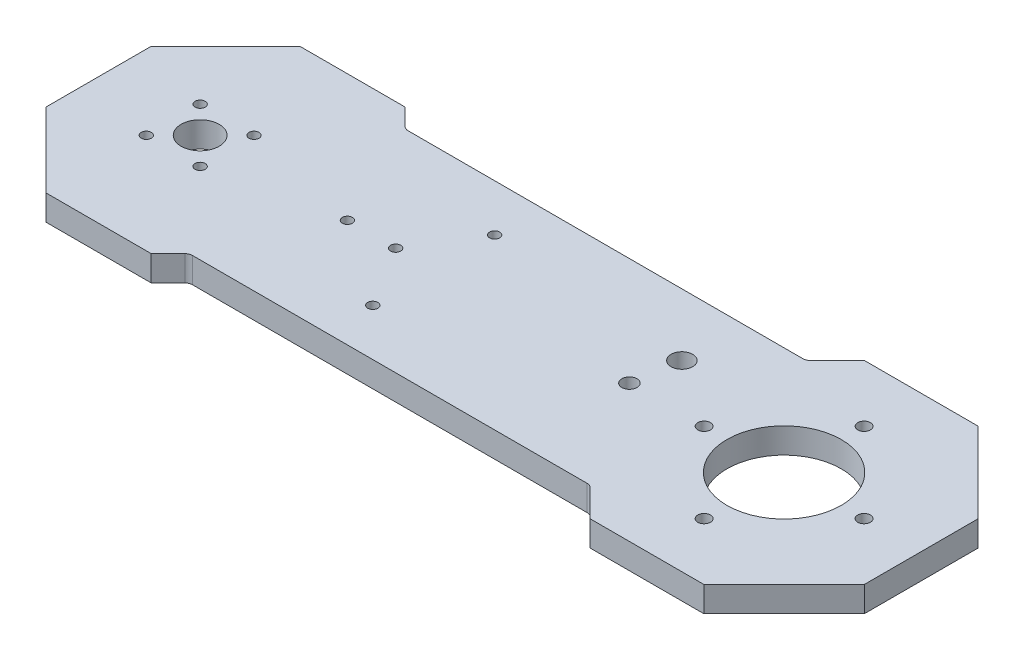
SolidWorks part; units mm, degrees
ref_plane "Спереди" through (0, 0, 0) normal (0, 0, 1) x (1, 0, 0)
ref_plane "Сверху" through (0, 0, 0) normal (0, 1, 0) x (1, 0, 0)
ref_plane "Справа" through (0, 0, 0) normal (1, 0, 0) x (0, 0, -1)
sketch "Эскиз1" plane through (0, 0, 0) normal (0, 1, 0) x (1, 0, 0)
  line L0 (-104.8938, 0) -> (200.5194, 0) construction
  line L1 (-172.6821, 42.5) -> (-12.3342, 42.5)
  line L2 (-172.6821, -42.5) -> (-12.3342, -42.5)
  line L4 (-172.6821, -42.5) -> (-172.6821, 42.5) construction
  arc A0 (-172.6821, 42.5) -> (-172.6821, -42.5) centre (-199.0213, 0) ccw
  arc A2 (-12.3342, -42.5) -> (-12.3342, 42.5) centre (20.9787, 0) ccw
  dimension "D1" = 220
  dimension "D2" = 108
  dimension "D3" = 100
  dimension "D4" = 85
extrude "Бобышка-Вытянуть1" add sketch "Эскиз1" along normal blind 10
sketch "Эскиз2" plane through (0, 10, 0) normal (0, 1, 0) x (1, 0, 0)
  line L0 (20.9787, 31.5) -> (20.9787, -31.5) construction
  line L1 (20.9787, -31.5) -> (52.4787, 0) construction
  line L2 (52.4787, 0) -> (-10.5213, 0) construction
  circle A0 centre (20.9787, 0) radius 31.5 construction
  circle A1 centre (20.9787, 31.5) radius 2.5
  circle A2 centre (-10.5213, 0) radius 2.5
  circle A3 centre (20.9787, -31.5) radius 2.5
  circle A4 centre (52.4787, 0) radius 2.5
  dimension "D1" = 63
  dimension "D2" = 5
  dimension "D3" = 5
  dimension "D4" = 5
  dimension "D5" = 5
extrude "Вырез-Вытянуть1" cut sketch "Эскиз2" against normal blind 10
chamfer "Фаска1" distance 2 angle 45 4 edges at (52.4787, 0, 2.5) (20.9787, 0, -29) (-10.5213, 0, 2.5) (20.9787, 0, 34)
sketch "Эскиз4" plane through (0, 0, 0) normal (0, -1, 0) x (1, 0, 0)
  circle A0 centre (20.9787, 0) radius 22.5
  dimension "D1" = 45
extrude "Вырез-Вытянуть3" cut sketch "Эскиз4" against normal blind 36
sketch "Эскиз6" plane through (0, 0, 0) normal (0, -1, 0) x (1, 0, 0)
  line L5 (-249.0213, 0) -> (74.9787, 0) construction
  arc A0 (-172.6821, 42.5) -> (-172.6821, -42.5) centre (-199.0213, 0) ccw construction
  arc A1 (-12.3342, -42.5) -> (-12.3342, 42.5) centre (20.9787, 0) ccw construction
  circle A2 centre (20.9787, 0) radius 22.5 construction
  circle A5 centre (-209.0213, 0) radius 7.5
  dimension "D1" = 230
  dimension "D7" = 15
sketch "Эскиз9" plane through (0, 10, 0) normal (0, 1, 0) x (1, 0, 0)
  line L0 (-39.952, -42.5) -> (-39.952, 42.5) construction
  line L1 (-172.6821, -42.5) -> (-12.3342, -42.5) construction
  line L2 (-12.3342, 42.5) -> (-172.6821, 42.5) construction
  line L3 (-39.952, 0) -> (-61.9777, 0) construction
  circle A0 centre (-39.952, 0) radius 3
  dimension "D1" = 6
extrude "Вырез-Вытянуть8" cut sketch "Эскиз9" against normal blind 13
sketch "Эскиз10" plane through (0, 10, 0) normal (0, 1, 0) x (1, 0, 0)
  circle A0 centre (-37.3333, 18.0546) radius 4.25
extrude "Вырез-Вытянуть9" cut sketch "Эскиз10" against normal blind 13
chamfer "Фаска6" distance 1 angle 45 1 edges at (-37.3333, 0, -13.8046)
extrude "Вырез-Вытянуть10" cut sketch "Эскиз6" against normal blind 10
sketch "Эскиз11" plane through (0, 0, 0) normal (0, -1, 0) x (1, 0, 0)
  line L0 (-117.0213, 24) -> (-117.0213, -24) construction
  line L1 (-209.0213, 0) -> (20.9787, 0) construction
  circle A0 centre (-117.0213, 24) radius 2
  circle A1 centre (-117.0213, -24) radius 2
  circle A2 centre (-209.0213, 0) radius 7.5 construction
  dimension "D1" = 4
  dimension "D2" = 4
  dimension "D3" = 48
  dimension "D4" = 24
  dimension "D5" = 92
extrude "Вырез-Вытянуть11" cut sketch "Эскиз11" against normal blind 15
sketch "Эскиз12" plane through (0, 0, 0) normal (0, -1, 0) x (1, 0, 0)
  line L1 (-209.0213, 0) -> (-132.0213, 0) construction
  circle A0 centre (-151.0213, 0) radius 2
  circle A1 centre (-132.0213, 0) radius 2
  circle A2 centre (-209.0213, 0) radius 7.5 construction
  dimension "D1" = 4
  dimension "D2" = 4
  dimension "D3" = 19
  dimension "D4" = 58
extrude "Вырез-Вытянуть12" cut sketch "Эскиз12" against normal blind 15
sketch "Эскиз13" plane through (0, 0, 0) normal (0, -1, 0) x (-1, 0, 0)
  line L0 (249.0213, 0) -> (-74.9787, 0) construction
  line L1 (209.0213, 15) -> (209.0213, -15) construction
  line L2 (209.0213, 0) -> (219.6279, 10.6066) construction
  line L3 (219.6279, 10.6066) -> (198.4147, 10.6066) construction
  line L4 (198.4147, 10.6066) -> (209.0213, 0) construction
  line L5 (209.0213, 0) -> (198.4147, -10.6066) construction
  line L6 (198.4147, -10.6066) -> (219.6279, -10.6066) construction
  line L7 (219.6279, -10.6066) -> (209.0213, 0) construction
  arc A0 (172.6821, -42.5) -> (172.6821, 42.5) centre (199.0213, 0) ccw construction
  arc A1 (12.3342, 42.5) -> (12.3342, -42.5) centre (-20.9787, 0) ccw construction
  circle A4 centre (219.6279, -10.6066) radius 2
  circle A5 centre (198.4147, -10.6066) radius 2
  circle A6 centre (219.6279, 10.6066) radius 2
  circle A7 centre (198.4147, 10.6066) radius 2
  circle A8 centre (209.0213, 0) radius 15 construction
  dimension "D1" = 45
  dimension "D5" = 4
  dimension "D6" = 4
  dimension "D7" = 4
  dimension "D8" = 4
  dimension "D9" = 30
extrude "Вырез-Вытянуть13" cut sketch "Эскиз13" against normal blind 10
sketch "Эскиз14" plane through (0, 0, 0) normal (0, -1, 0) x (-1, 0, 0)
  line L0 (249.0213, 0) -> (-74.9787, 0) construction
  line L1 (170.8106, -42.5) -> (12.8888, -42.5)
  line L2 (-43.3462, -54) -> (1.3888, -54)
  line L3 (1.3888, -54) -> (12.8888, -42.5)
  line L5 (12.8888, 42.5) -> (1.3888, 54)
  line L6 (1.3888, 54) -> (-43.3462, 54)
  line L7 (-43.3462, 54) -> (-74.9787, 22.3675)
  line L8 (-74.9787, 22.3675) -> (-74.9787, -22.3675)
  line L9 (-74.9787, -22.3675) -> (-43.3462, -54)
  line L10 (178.3106, -50) -> (219.732, -50)
  line L11 (219.732, -50) -> (249.0213, -20.7107)
  line L12 (249.0213, -20.7107) -> (249.0213, 20.7107)
  line L13 (249.0213, 20.7107) -> (219.732, 50)
  line L14 (219.732, 50) -> (178.3106, 50)
  line L15 (178.3106, 50) -> (170.8106, 42.5)
  line L17 (170.8106, -42.5) -> (178.3106, -50)
  line L18 (172.6821, -42.5) -> (12.3342, -42.5) construction
  line L19 (170.8106, 42.5) -> (12.8888, 42.5)
  line L20 (12.3342, 42.5) -> (172.6821, 42.5) construction
  line L24 (149.0213, 0) -> (149.0213, -20.7107) [skipped]
  line L25 (33.0213, -22.3675) -> (33.0213, 0) [skipped]
  arc A0 (172.6821, -42.5) -> (172.6821, 42.5) centre (199.0213, 0) ccw construction
  arc A1 (12.3342, 42.5) -> (12.3342, -42.5) centre (-20.9787, 0) ccw construction
  circle A2 centre (-20.9787, 0) radius 54 construction
  circle A3 centre (199.0213, 0) radius 50 construction
  circle A4 centre (-20.9787, 0) radius 22.5
  circle A5 centre (37.3333, 18.0546) radius 4.25
  circle A6 centre (10.5213, 0) radius 2.5
  circle A7 centre (-52.4787, 0) radius 2.5
  circle A8 centre (-20.9787, 31.5) radius 2.5
  circle A9 centre (-20.9787, -31.5) radius 2.5
  circle A10 centre (39.952, 0) radius 3
  circle A11 centre (117.0213, 24) radius 2
  circle A12 centre (132.0213, 0) radius 2
  circle A13 centre (117.0213, -24) radius 2
  circle A14 centre (151.0213, 0) radius 2
  circle A15 centre (198.4147, -10.6066) radius 2
  circle A16 centre (198.4147, 10.6066) radius 2
  circle A17 centre (209.0213, 0) radius 7.5
  circle A18 centre (219.6279, 10.6066) radius 2
  circle A19 centre (219.6279, -10.6066) radius 2
  dimension "D1" = 108
  dimension "D2" = 100
extrude "Бобышка-Вытянуть2" add sketch "Эскиз14" against normal blind 10
chamfer "Фаска7" distance 2.9 angle 45 4 edges at (20.9787, 0, -34) (-10.5213, 0, -2.5) (52.4787, 0, -2.5) (20.9787, 0, 29)
chamfer "Фаска8" distance 1.9 angle 45 4 edges at (-198.4147, 0, -12.6066) (-198.4147, 0, 8.6066) (-219.6279, 0, -12.6066) (-219.6279, 0, 8.6066)
fillet "Скругление2" radius 3 4 edges at (-12.8888, 5, -42.5) (-170.8106, 5, -42.5) (-170.8106, 5, 42.5) (-12.8888, 5, 42.5)
